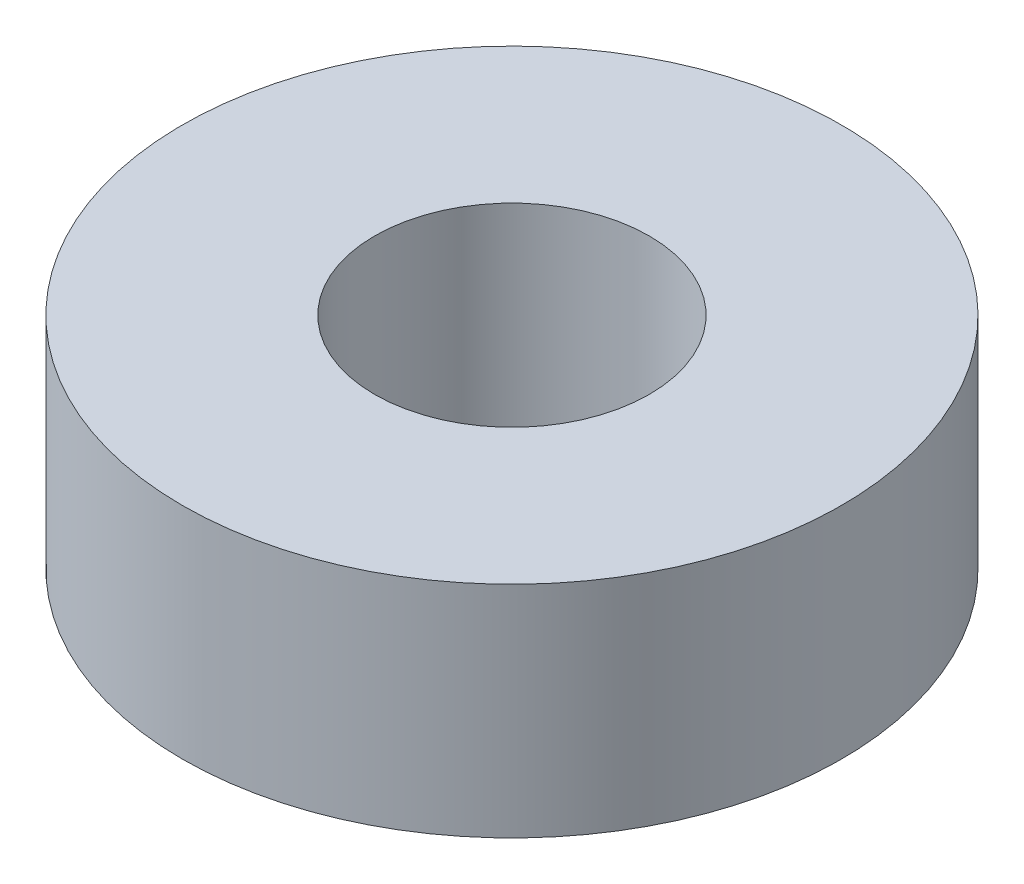
SolidWorks part; units mm, degrees
ref_plane "Front Plane" through (0, 0, 0) normal (0, 0, 1) x (1, 0, 0)
ref_plane "Top Plane" through (0, 0, 0) normal (0, 1, 0) x (1, 0, 0)
ref_plane "Right Plane" through (0, 0, 0) normal (1, 0, 0) x (0, 0, -1)
sketch "Sketch1" plane through (0, 0, 0) normal (0, 1, 0) x (1, 0, 0)
  circle A0 centre (0, 0) radius 6
  circle A1 centre (0, 0) radius 2.5
  dimension "D1" = 5
  dimension "D2" = 12
extrude "Boss-Extrude1" add sketch "Sketch1" along normal blind 4
